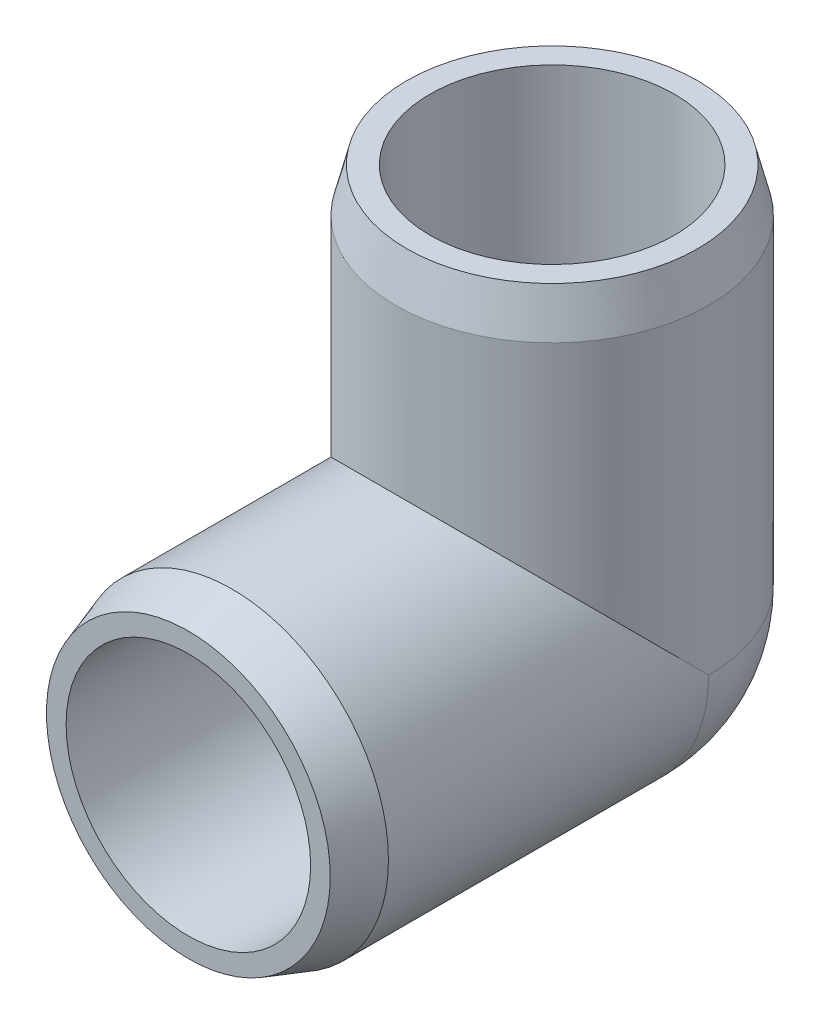
SolidWorks part; units mm, degrees
ref_plane "Front Plane" through (0, 0, 0) normal (0, 0, 1) x (1, 0, 0)
ref_plane "Top Plane" through (0, 0, 0) normal (0, 1, 0) x (1, 0, 0)
ref_plane "Right Plane" through (0, 0, 0) normal (1, 0, 0) x (0, 0, -1)
sketch "Sketch2" plane through (0, 0, 0) normal (0, 0, 1) x (1, 0, 0)
  line L0 (-13.2672, 0) -> (17.6518, 0) construction
  line L1 (13.6525, 13.6525) -> (13.6525, 45.4025)
  line L2 (13.6525, 45.4025) -> (0, 45.4025) construction
  line L3 (0, 45.4025) -> (0, 0) construction
  line L4 (0, 50.4549) -> (0, -7.2494) construction
  line L5 (10.668, 45.4025) -> (10.668, 13.6525)
  line L6 (13.6525, 13.6525) -> (3.2844, 13.6525) construction
  line L7 (0, 2.9845) -> (-10.0793, 2.9845) construction
  line L8 (13.6525, 45.4025) -> (10.668, 45.4025)
  line L9 (0, 0) -> (0, 2.9845)
  arc A0 (0, 0) -> (13.6525, 13.6525) centre (0, 13.6525) ccw
  arc A1 (10.668, 13.6525) -> (0, 2.9845) centre (0, 13.6525) cw
  dimension "D1" = 45.4025
  dimension "D2" = 13.6525
  dimension "D3" = 10.668
revolve "Revolve1" add sketch "Sketch2" angle 360 about L4
ref_plane "Plane1" through (0, 0, 31.75) normal (0, 0, -1) x (-1, 0, 0)
sketch "Sketch5" plane through (0, 0, 31.75) normal (0, 0, -1) x (-1, 0, 0)
  circle A0 centre (0, 13.6525) radius 13.6525
  circle A1 centre (0, 13.6525) radius 10.668
  point P2 (0, 0)
  dimension "D2" = 27.305
  dimension "D3" = 21.336
  dimension "D1" = 13.6525
extrude "Boss-Extrude2" add sketch "Sketch5" along normal up to surface (31.75 mm away)
ref_plane "Plane2" through (0, 13.6525, 0) normal (0, 1, 0) x (1, 0, 0)
sketch "Sketch6" plane through (0, 13.6525, 0) normal (0, 1, 0) x (1, 0, 0)
  circle A0 centre (0, 0) radius 10.668
  dimension "D1" = 21.336
extrude "Cut-Extrude1" cut sketch "Sketch6" along normal blind 43.688
ref_plane "Plane3" through (0, 0, 0) normal (0, 0, 1) x (1, 0, 0)
sketch "Sketch7" plane through (0, 0, 0) normal (0, 0, 1) x (1, 0, 0)
  line L0 (0, 0) -> (0, 13.6525) construction
  circle A0 centre (0, 13.6525) radius 10.668
  dimension "D1" = 21.336
extrude "Cut-Extrude2" cut sketch "Sketch7" along normal blind 44.196
sketch "Sketch8" plane through (0, 0, 0) normal (0, 0, 1) x (1, 0, 0)
  line L0 (10.668, 45.4025) -> (-10.668, 45.4025) construction
  line L1 (10.668, 45.4025) -> (-10.668, 45.4025) construction
  line L2 (-10.668, 45.4025) -> (-10.668, 26.3525) construction
  line L3 (-10.668, 26.3525) -> (-9.398, 26.3525)
  line L4 (-9.398, 26.3525) -> (-9.398, 24.4475)
  line L5 (-9.398, 24.4475) -> (-10.668, 24.4475)
  line L6 (-10.668, 24.4475) -> (-10.668, 26.3525)
  line L7 (0, 45.4025) -> (0, 22.7519) construction
  dimension "D1" = 19.05
  dimension "D2" = 1.27
  dimension "D3" = 1.905
revolve "Revolve2" add sketch "Sketch8" angle 360 about L7
sketch "Sketch9" plane through (0, 0, 0) normal (1, 0, 0) x (0, 0, -1)
  line L0 (-31.75, 24.3205) -> (-31.75, 2.9845) construction
  line L1 (-31.75, 24.3205) -> (-31.75, 2.9845) construction
  line L2 (-31.75, 2.9845) -> (-12.7, 2.9845) construction
  line L3 (-12.7, 2.9845) -> (-12.7, 4.2545)
  line L4 (-12.7, 4.2545) -> (-10.795, 4.2545)
  line L5 (-10.795, 4.2545) -> (-10.795, 2.9845)
  line L6 (-10.795, 2.9845) -> (-12.7, 2.9845)
  line L7 (-31.75, 13.6525) -> (-2.1918, 13.6525) construction
  dimension "D1" = 19.05
  dimension "D2" = 1.27
  dimension "D3" = 1.905
revolve "Revolve3" add sketch "Sketch9" angle 360 about L7
sketch "Sketch10" plane through (0, 0, 0) normal (1, 0, 0) x (0, 0, -1)
  line L0 (13.6525, 45.4025) -> (-13.6525, 45.4025) construction
  line L1 (13.6525, 45.4025) -> (-13.6525, 45.4025) construction
  line L2 (13.6525, 45.4025) -> (13.6525, 41.5925)
  line L3 (13.6525, 13.6525) -> (13.6525, 45.4025) construction
  line L4 (13.6525, 45.4025) -> (12.7, 45.4025)
  line L5 (12.7, 45.4025) -> (13.6525, 41.5925)
  line L6 (0, 45.4025) -> (0, 29.8016) construction
  dimension "D1" = 3.81
  dimension "D2" = 0.9525
revolve "Cut-Revolve1" cut sketch "Sketch10" angle 360 about L6
sketch "Sketch12" plane through (0, 13.6525, 0) normal (0, 1, 0) x (1, 0, 0)
  line L0 (-13.6525, -31.75) -> (13.6525, -31.75) construction
  line L1 (-13.6525, -31.75) -> (13.6525, -31.75) construction
  line L2 (-13.6525, -31.75) -> (-13.6525, -27.94)
  line L3 (-13.6525, 0) -> (-13.6525, -31.75) construction
  line L4 (-13.6525, -31.75) -> (-12.3825, -31.75)
  line L5 (-12.3825, -31.75) -> (-13.6525, -27.94)
  line L6 (0, -31.75) -> (0, -18.7799) construction
  dimension "D1" = 3.81
  dimension "D2" = 1.27
revolve "Cut-Revolve2" cut sketch "Sketch12" angle 360 about L6
